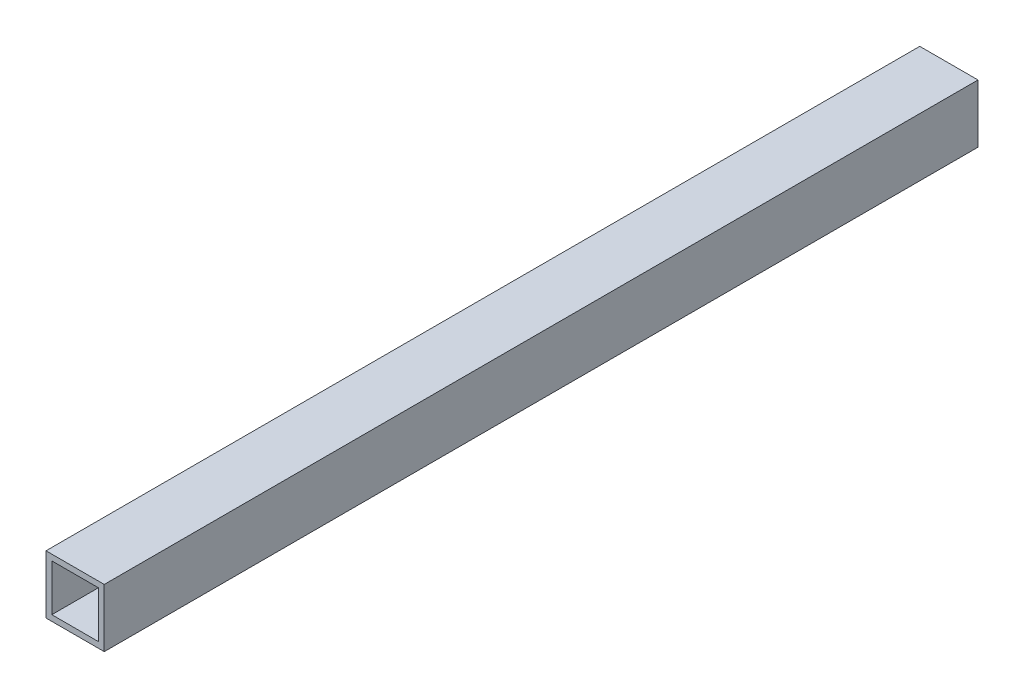
SolidWorks part; units mm, degrees
ref_plane "前视基准面" through (0, 0, 0) normal (0, 0, 1) x (1, 0, 0)
ref_plane "上视基准面" through (0, 0, 0) normal (0, 1, 0) x (1, 0, 0)
ref_plane "右视基准面" through (0, 0, 0) normal (1, 0, 0) x (0, 0, -1)
sketch "草图1" plane through (0, 0, 0) normal (0, 0, 1) x (1, 0, 0)
  line L1 (-5, 5) -> (5, 5)
  line L2 (-5, 5) -> (-5, -5)
  line L3 (-5, -5) -> (5, -5)
  line L4 (5, 5) -> (5, -5)
  line L5 (-5, 5) -> (5, -5) construction
  line L6 (-5, -5) -> (5, 5) construction
  line L7 (-4, 4) -> (4, 4)
  line L8 (-4, 4) -> (-4, -4)
  line L9 (-4, -4) -> (4, -4)
  line L10 (4, 4) -> (4, -4)
  line L11 (-4, 4) -> (4, -4) construction
  line L12 (-4, -4) -> (4, 4) construction
  point P0 (0, 0)
  point P5 (0, 0)
  dimension "D1" = 10
  dimension "D2" = 10
  dimension "D3" = 8
  dimension "D4" = 8
extrude "凸台-拉伸1" add sketch "草图1" along normal blind 150
